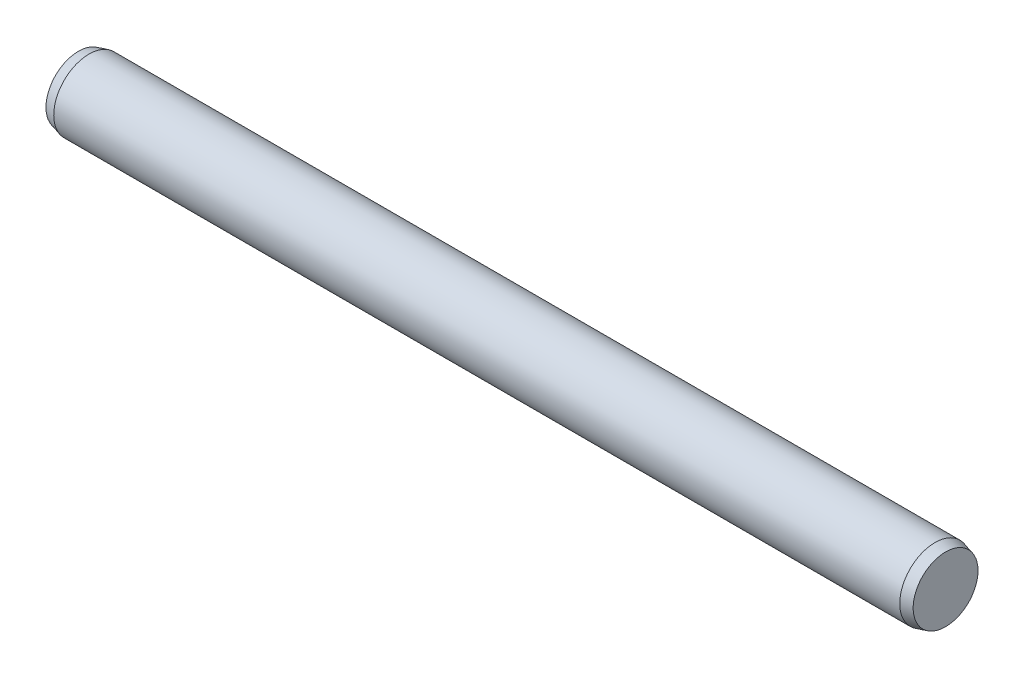
SolidWorks part; units mm, degrees
ref_plane "Front Plane" through (0, 0, 0) normal (0, 0, 1) x (1, 0, 0)
ref_plane "Top Plane" through (0, 0, 0) normal (0, 1, 0) x (1, 0, 0)
ref_plane "Right Plane" through (0, 0, 0) normal (1, 0, 0) x (0, 0, -1)
sketch "Sketch1" plane through (0, 0, 0) normal (0, 0, 1) x (1, 0, 0)
  line L0 (-12, 0) -> (12, 0) construction
  line L1 (12, 1) -> (12, -1) construction
  line L2 (-12, 1) -> (-12, -1) construction
  line L3 (12.3, 1) -> (12.3, -1) construction
  line L4 (-12.3, 1) -> (-12.3, -1) construction
  line L5 (-12, 0) -> (-12.3, 0) construction
  line L6 (12, 0) -> (12.3, 0) construction
  dimension "D1" = 0.3
  dimension "Dia" = 2
  dimension "Length" = 24
  dimension "C" = 0.3
sketch "Sketch2" plane through (0, 0, 0) normal (1, 0, 0) x (0, 0, -1)
  circle A0 centre (0, 0) radius 1
extrude "Extrude1" add sketch "Sketch2" against normal up to vertex (12 mm away) and the other way up to vertex (12 mm away) up to point (-12, 1, 0) other way up to point (12, 1, 0)
sketch "Sketch3" plane through (12, 0, 0) normal (1, 0, 0) x (0, 0, -1)
  circle A1 centre (0, 0) radius 1
  circle A2 centre (0, 0) radius 1
  dimension "D1" = 0
extrude "Extrude2" add sketch "Sketch3" along normal up to vertex (0.3 mm away) draft 15 up to point (12.3, 0, 0)
sketch "Sketch4" plane through (-12, 0, 0) normal (-1, 0, 0) x (0, 0, 1)
  circle A1 centre (0, 0) radius 1
  circle A2 centre (0, 0) radius 1
  dimension "D1" = 0
extrude "Extrude3" add sketch "Sketch4" along normal up to vertex (0.3 mm away) draft 15 up to point (-12.3, 0, 0)
equation "\"D1@Sketch1\" = \"C@Sketch1\""
